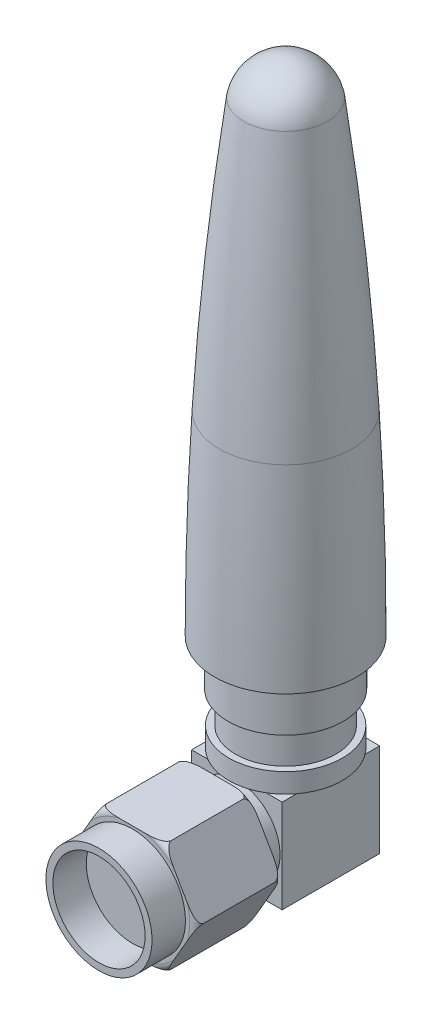
SolidWorks part; units mm, degrees
ref_plane "Front" through (0, 0, 0) normal (0, 0, 1) x (1, 0, 0)
ref_plane "Top" through (0, 0, 0) normal (0, 1, 0) x (1, 0, 0)
ref_plane "Side" through (0, 0, 0) normal (1, 0, 0) x (0, 0, -1)
sketch "Sketch1" plane through (0, 0, 0) normal (0, 0, 1) x (1, 0, 0)
  circle A0 centre (0, 0) radius 3.81
  circle A1 centre (0, 0) radius 3.31
  dimension "D1" = 7.62
  dimension "D2" = 0.5
extrude "Boss-Extrude1" add sketch "Sketch1" along normal blind 2.4
sketch "Sketch2" plane through (0, 0, 0) normal (0, 0, -1) x (-1, 0, 0)
  line L1 (2.3094, -4) -> (4.6188, 0)
  line L2 (4.6188, 0) -> (2.3094, 4)
  line L3 (2.3094, 4) -> (-2.3094, 4)
  line L4 (-2.3094, 4) -> (-4.6188, 0)
  line L5 (-4.6188, 0) -> (-2.3094, -4)
  line L6 (-2.3094, -4) -> (2.3094, -4)
  circle A0 centre (0, 0) radius 4 construction
  point P1 (0, 0)
  dimension "D1" = 8
extrude "Boss-Extrude2" add sketch "Sketch2" along normal blind 6.1
sketch "Sketch3" plane through (0, 0, 0) normal (0, 1, 0) x (1, 0, 0)
  line L0 (0, 0) -> (0, 6.1) construction
  line L1 (-3.81, 0) -> (3.81, 0) construction
  line L2 (-2.3094, 6.1) -> (2.3094, 6.1) construction
  line L3 (-4.6188, 3.05) -> (-3.4875, 3.05) construction
  line L4 (-4.6188, 6.1) -> (-2.3094, 6.1) construction
  line L5 (-4.6188, 6.1) -> (-4.6188, 0) construction
  line L6 (-4.6188, 5.6) -> (-4.6188, 6.1)
  line L7 (-4.6188, 6.1) -> (-4.1188, 6.1)
  line L8 (-4.6188, 0) -> (-4.1188, 0)
  line L9 (-4.6188, 0.5) -> (-4.6188, 0)
  arc A0 (-4.1188, 6.1) -> (-4.6188, 5.6) centre (-4.1188, 5.6) ccw
  arc A1 (-4.1188, 0) -> (-4.6188, 0.5) centre (-4.1188, 0.5) cw
  dimension "D1" = 0.5
revolve "Cut-Revolve1" cut sketch "Sketch3" angle 360 about L0
sketch "Sketch4" plane through (0, 0, -6.1) normal (0, 0, -1) x (-1, 0, 0)
  circle A0 centre (0, 0) radius 3.1
  dimension "D1" = 6.2
extrude "Boss-Extrude3" add sketch "Sketch4" along normal blind 1.4
sketch "Sketch5" plane through (0, 0, -7.5) normal (0, 0, -1) x (-1, 0, 0)
  line L1 (-3.25, 3.35) -> (3.25, 3.35)
  line L2 (-3.25, 3.35) -> (-3.25, -3.35)
  line L3 (-3.25, -3.35) -> (3.25, -3.35)
  line L4 (3.25, 3.35) -> (3.25, -3.35)
  line L5 (-3.25, 3.35) -> (3.25, -3.35) construction
  line L6 (-3.25, -3.35) -> (3.25, 3.35) construction
  point P0 (0, 0)
  dimension "D1" = 6.5
  dimension "D2" = 6.7
extrude "Boss-Extrude4" add sketch "Sketch5" along normal blind 7
sketch "Sketch6" plane through (0, 0, -14.5) normal (0, 0, -1) x (-1, 0, 0)
  circle A0 centre (0, 0) radius 2.5
  circle A1 centre (0, 0) radius 2.45
  dimension "D1" = 5
  dimension "D2" = 0.05
extrude "Cut-Extrude1" cut sketch "Sketch6" against normal blind 7
sketch "Sketch7" plane through (0, 0, -14.5) normal (0, 0, -1) x (-1, 0, 0)
  line L0 (1.4622, 2.0278) -> (-2.0278, -1.4622)
  line L1 (-1.4622, -2.0278) -> (2.0278, 1.4622)
  line L2 (-0.2828, 0.2828) -> (0.2828, -0.2828) construction
  line L3 (3.25, 3.35) -> (-3.25, 3.35) construction
  circle A0 centre (0, 0) radius 2.5 construction
  arc A1 (-2.0278, -1.4622) -> (-1.4622, -2.0278) centre (0, 0) ccw
  arc A2 (2.0278, 1.4622) -> (1.4622, 2.0278) centre (0, 0) ccw
  point P8 (0, 0)
  dimension "D1" = 0.8
  dimension "D2" = 45
extrude "Cut-Extrude2" cut sketch "Sketch7" against normal blind 0.5
sketch "Sketch8" plane through (0, 3.35, 0) normal (0, 1, 0) x (1, 0, 0)
  line L0 (3.25, 14.5) -> (-3.25, 7.5) construction
  circle A0 centre (0, 11) radius 4.075
  dimension "D1" = 8.15
extrude "Boss-Extrude5" add sketch "Sketch8" along normal blind 1.4
sketch "Sketch9" plane through (0, 4.75, 0) normal (0, 1, 0) x (1, 0, 0)
  circle A0 centre (0, 11) radius 3.6
  dimension "D1" = 7.2
extrude "Boss-Extrude6" add sketch "Sketch9" along normal blind 2.3
sketch "Sketch10" plane through (0, 7.05, 0) normal (0, 1, 0) x (1, 0, 0)
  circle A0 centre (0, 11) radius 4.125
  dimension "D1" = 8.25
extrude "Boss-Extrude7" add sketch "Sketch10" along normal blind 3.25
sketch "Sketch11" plane through (0, 0, 0) normal (1, 0, 0) x (0, 0, -1)
  line L0 (11, 10.3) -> (11, 46.3) construction
  line L1 (15.125, 10.3) -> (6.875, 10.3) construction
  line L2 (11, 10.3) -> (5.9, 10.3)
  line L3 (11, 10.3) -> (11, 46.3)
  arc A0 (11, 46.3) -> (8, 43.8) centre (11, 43.25) ccw
  arc A1 (8, 43.8) -> (6.25, 24.3) centre (253.7431, 11.9176) ccw
  arc A2 (5.9, 10.3) -> (6.25, 24.3) centre (286.075, 10.3) cw
  point P10 (6.25, 31.0459)
  point P11 (6.178, 30.2893)
  dimension "D1" = 36
  dimension "D2" = 2.5
  dimension "D3" = 3
  dimension "D4" = 14
  dimension "D5" = 4.75
  dimension "D6" = 5.1
revolve "Revolve1" add sketch "Sketch11" angle 360 about L0
equation "\"0.3inch\"=7.64"
